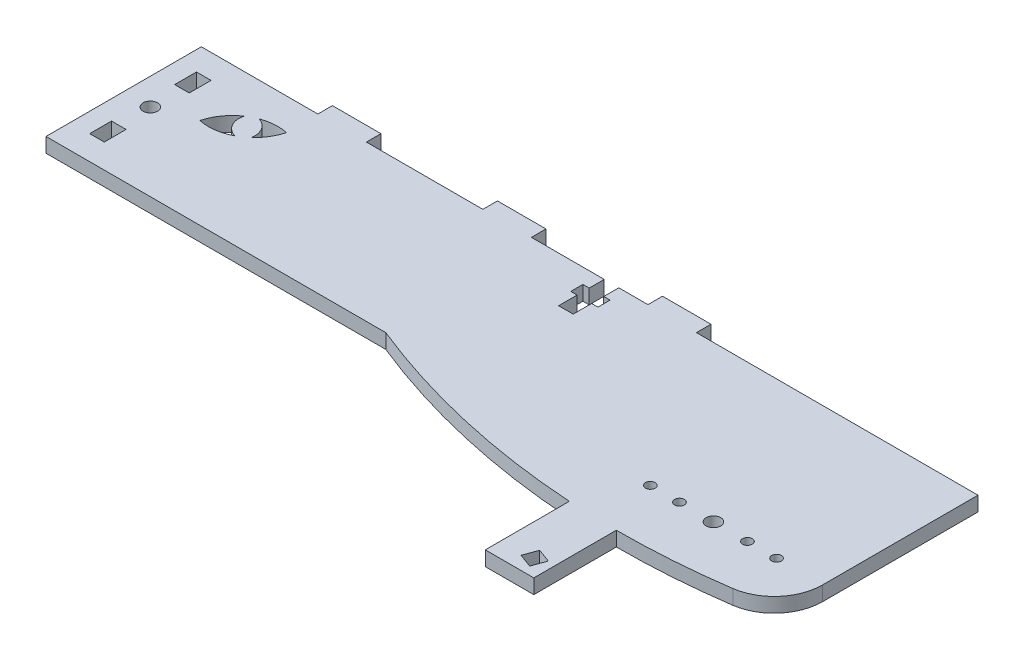
SolidWorks part; units mm, degrees
ref_plane "Front Plane" through (0, 0, 0) normal (0, 0, 1) x (1, 0, 0)
ref_plane "Top Plane" through (0, 0, 0) normal (0, 1, 0) x (1, 0, 0)
ref_plane "Right Plane" through (0, 0, 0) normal (1, 0, 0) x (0, 0, -1)
sketch "Sketch2" plane through (0, 0, 0) normal (0, 1, 0) x (1, 0, 0)
  line L0 (-22.5, 40.4168) -> (-22.5, -23.5832) construction
  line L1 (-90, 8.4168) -> (-160, 8.4168)
  line L2 (0, 8.4168) -> (0, 40.4168)
  line L3 (0, 40.4168) -> (-58, 40.4168)
  line L4 (-160, 8.4168) -> (-160, 40.4168)
  line L5 (-160, 24.4168) -> (-154.5, 24.4168) construction
  line L6 (-156, 35.4168) -> (-156, 30.9168)
  line L7 (-156, 30.9168) -> (-153, 30.9168)
  line L8 (-153, 30.9168) -> (-153, 35.4168)
  line L9 (-153, 35.4168) -> (-156, 35.4168)
  line L10 (-156, 13.4168) -> (-156, 17.9168)
  line L11 (-153, 13.4168) -> (-156, 13.4168)
  line L12 (-153, 17.9168) -> (-153, 13.4168)
  line L13 (-156, 17.9168) -> (-153, 17.9168)
  line L14 (-136, 40.4168) -> (-136, 43.4168)
  line L15 (-136, 43.4168) -> (-126, 43.4168)
  line L16 (-126, 43.4168) -> (-126, 40.4168)
  line L17 (-136, 40.4168) -> (-160, 40.4168)
  line L18 (-92, 43.4168) -> (-92, 40.4168)
  line L19 (-102, 43.4168) -> (-92, 43.4168)
  line L20 (-102, 40.4168) -> (-102, 43.4168)
  line L21 (-58, 43.4168) -> (-58, 40.4168)
  line L22 (-68, 43.4168) -> (-58, 43.4168)
  line L23 (-68, 40.4168) -> (-68, 43.4168)
  line L27 (-102, 40.4168) -> (-126, 40.4168)
  line L28 (-68, 40.4168) -> (-74, 40.4168)
  line L30 (-24, 43.4168) -> (-24, 40.4168) [skipped]
  line L31 (-34, 43.4168) -> (-24, 43.4168) [skipped]
  line L32 (-34, 40.4168) -> (-34, 43.4168) [skipped]
  line L33 (-74, 40.4168) -> (-74, 37.3168)
  line L34 (-74, 37.3168) -> (-72.7, 37.3168)
  line L35 (-72.7, 37.3168) -> (-72.7, 34.8168)
  line L36 (-72.7, 34.8168) -> (-74, 34.8168)
  line L37 (-74, 34.8168) -> (-74, 31.0168)
  line L38 (-74, 31.0168) -> (-77, 31.0168)
  line L39 (-77, 31.0168) -> (-77, 34.8168)
  line L40 (-77, 34.8168) -> (-78.3, 34.8168)
  line L41 (-78.3, 34.8168) -> (-78.3, 37.3168)
  line L42 (-78.3, 37.3168) -> (-77, 37.3168)
  line L43 (-77, 37.3168) -> (-77, 40.4168)
  line L44 (-77, 40.4168) -> (-92, 40.4168)
  line L45 (-31, -3.0909) -> (-31, -20.0909)
  line L46 (-31, -20.0909) -> (-41, -20.0909)
  line L47 (-41, -20.0909) -> (-41, -2.7721)
  line L48 (-32.5, -15.5909) -> (-32.5, -20.0909) construction
  line L49 (-32.5, -15.5909) -> (-33.5261, -18.41)
  line L50 (-33.5261, -18.41) -> (-36.3451, -17.384)
  line L51 (-36.3451, -17.384) -> (-35.3191, -14.5649)
  line L52 (-35.3191, -14.5649) -> (-32.5, -15.5909)
  circle A1 centre (-22.5, 8.4168) radius 1.5
  circle A2 centre (-15.5, 8.4168) radius 1
  circle A3 centre (-29.5, 8.4168) radius 1
  circle A4 centre (-9.5, 8.4168) radius 1
  circle A5 centre (-35.5, 8.4168) radius 1
  arc A6 (-147, 27.1168) -> (-143.1981, 32.4685) centre (-137.9183, 24.6913) cw
  arc A7 (-147, 27.1168) -> (-140.6415, 27.9685) centre (-144.9938, 36.3002) ccw
  arc A8 (-143.1981, 32.4685) -> (-140.6415, 27.9685) centre (-139.6835, 31.489) ccw
  arc A9 (-141.1981, 33.5006) -> (-138.6415, 29.3714) centre (-142.2351, 30.0025) cw
  arc A10 (-141.1981, 33.5006) -> (-135.9121, 33.8748) centre (-137.9183, 24.6913) cw
  arc A11 (-138.6415, 29.3714) -> (-135.9121, 33.8748) centre (-144.9938, 36.3002) ccw
  arc A13 (-90, 8.4168) -> (-41, -2.7721) centre (-31, 153.9091) ccw
  arc A14 (-8.5714, -1.4806) -> (0, 8.4168) centre (-10, 8.4168) ccw
  circle A15 centre (-154.5, 24.4168) radius 1.5
  arc A16 (-31, -3.0909) -> (-8.5714, -1.4806) centre (-31, 153.9091) ccw
  point P5 (-22.5, 8.4168)
  point P8 (-154.5, 30.9168)
  point P17 (-147, 27.1168)
  point P20 (-135.9121, 33.8748)
  point P21 (-134.2493, 18.3796)
  point P32 (-136.9526, 22.817)
  point P35 (-90, 8.4168)
  point P40 (0, 0)
  point P47 (-136, 40.4168)
  point P55 (-74, 40.4168)
  point P82 (0, 0)
  dimension "D4" = 3
  dimension "D5" = 7
  dimension "D6" = 2
  dimension "D8" = 9.4
  dimension "D9" = 57
  dimension "D14" = 31
  dimension "D15" = 10
  dimension "D22" = 3
  dimension "D2" = 32
  dimension "D3" = 22.5
  dimension "D7" = 6
  dimension "D10" = 2
  dimension "D11" = 13.3
  dimension "D12" = 4.5
  dimension "D13" = 2
  dimension "D16" = 70
  dimension "D17" = 90
  dimension "D18" = 4
  dimension "D19" = 5
  dimension "D20" = 4.5
  dimension "D21" = 3
  dimension "D23" = 6.5
  dimension "D24" = 24
  dimension "D25" = 10
  dimension "D27" = 6
  dimension "D28" = 3.1
  dimension "D29" = 2.5
  dimension "D30" = 3.8
  dimension "D31" = 3
  dimension "D32" = 1.3
  dimension "D33" = 10
  dimension "D34" = 17
  dimension "D35" = 4.5
  dimension "D36" = 1.5
  dimension "D37" = 3
  dimension "D38" = 20
  dimension "D26" = 4
extrude "Boss-Extrude1" add sketch "Sketch2" along normal blind 3
